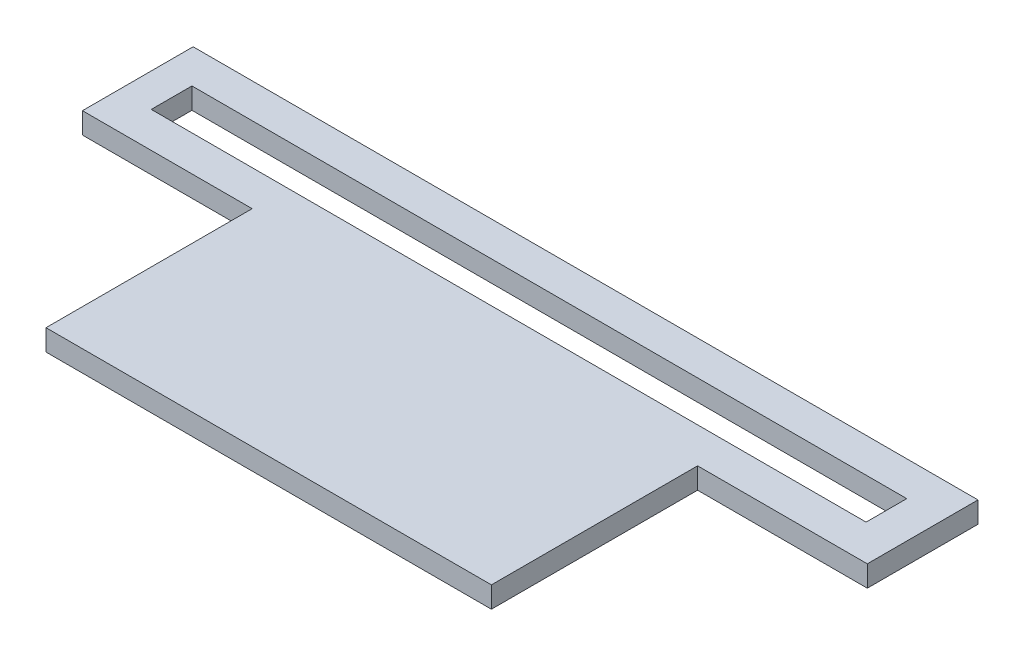
SolidWorks part; units mm, degrees
ref_plane "Plan de face" through (0, 0, 0) normal (0, 0, 1) x (1, 0, 0)
ref_plane "Plan de dessus" through (0, 0, 0) normal (0, 1, 0) x (1, 0, 0)
ref_plane "Plan de droite" through (0, 0, 0) normal (1, 0, 0) x (0, 0, -1)
sketch "Esquisse1" plane through (0, 0, 0) normal (0, 1, 0) x (1, 0, 0)
  line L9 (-34.5897, 18.206) -> (-34.5897, 28.006)
  line L14 (34.8903, 28.006) -> (34.8903, 18.206)
  line L15 (-19.5647, -0.044) -> (-19.5647, 18.206)
  line L16 (19.8653, -0.044) -> (19.8653, 18.206)
  line L17 (-34.5897, 18.206) -> (-19.5647, 18.206)
  line L18 (19.8653, 18.206) -> (34.8903, 18.206)
  line L20 (-19.5647, -0.044) -> (19.8653, -0.044)
  line L22 (-34.5897, 28.006) -> (34.8903, 28.006)
  line L34 (-31.64, 24.95) -> (31.64, 24.95)
  line L35 (-31.64, 24.95) -> (-31.64, 21.35)
  line L36 (-31.64, 21.35) -> (31.64, 21.35)
  line L37 (31.64, 24.95) -> (31.64, 21.35)
extrude "Boss.-Extru.3" add sketch "Esquisse1" along normal blind 1.87
